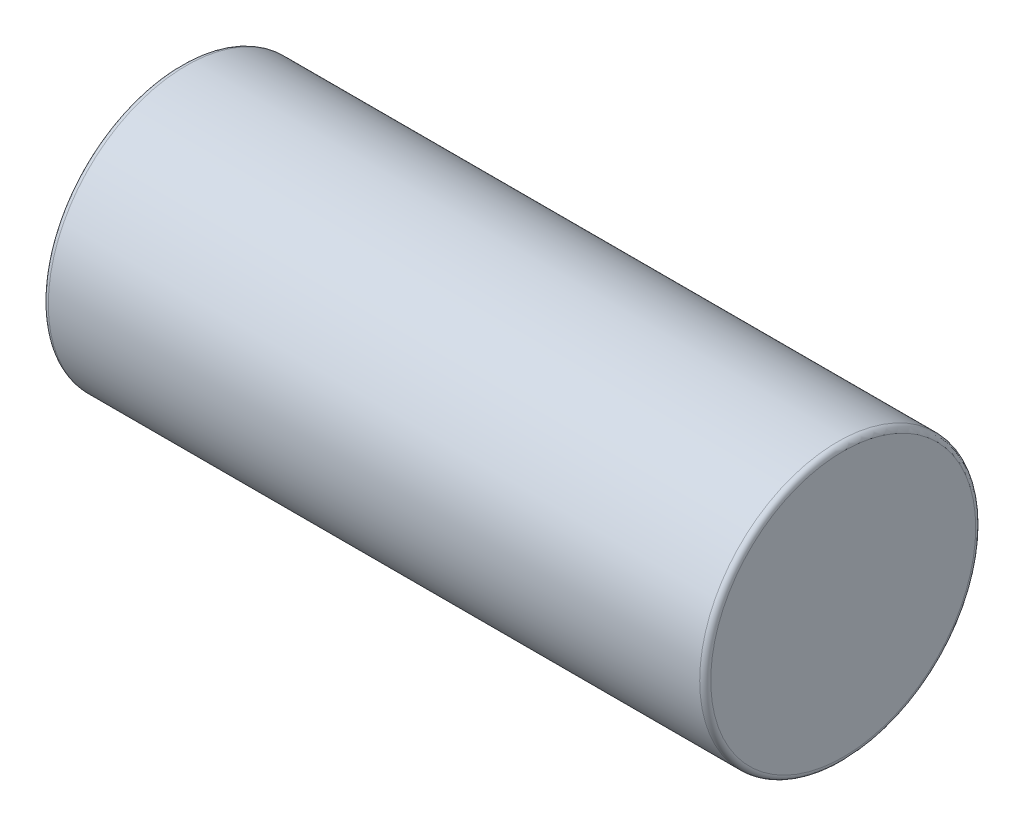
SolidWorks part; units mm, degrees
ref_plane "Front Plane" through (0, 0, 0) normal (0, 0, 1) x (1, 0, 0)
ref_plane "Top Plane" through (0, 0, 0) normal (0, 1, 0) x (1, 0, 0)
ref_plane "Right Plane" through (0, 0, 0) normal (1, 0, 0) x (0, 0, -1)
sketch "Sketch1" plane through (0, 0, 0) normal (1, 0, 0) x (0, 0, -1)
  circle A0 centre (0, 0) radius 63.5
  dimension "D1" = 127
extrude "Boss-Extrude1" add sketch "Sketch1" along normal mid plane 304.8
fillet "Fillet1" radius 2.54 2 edges at (-152.4, 0, -63.5) (152.4, 0, -63.5)
